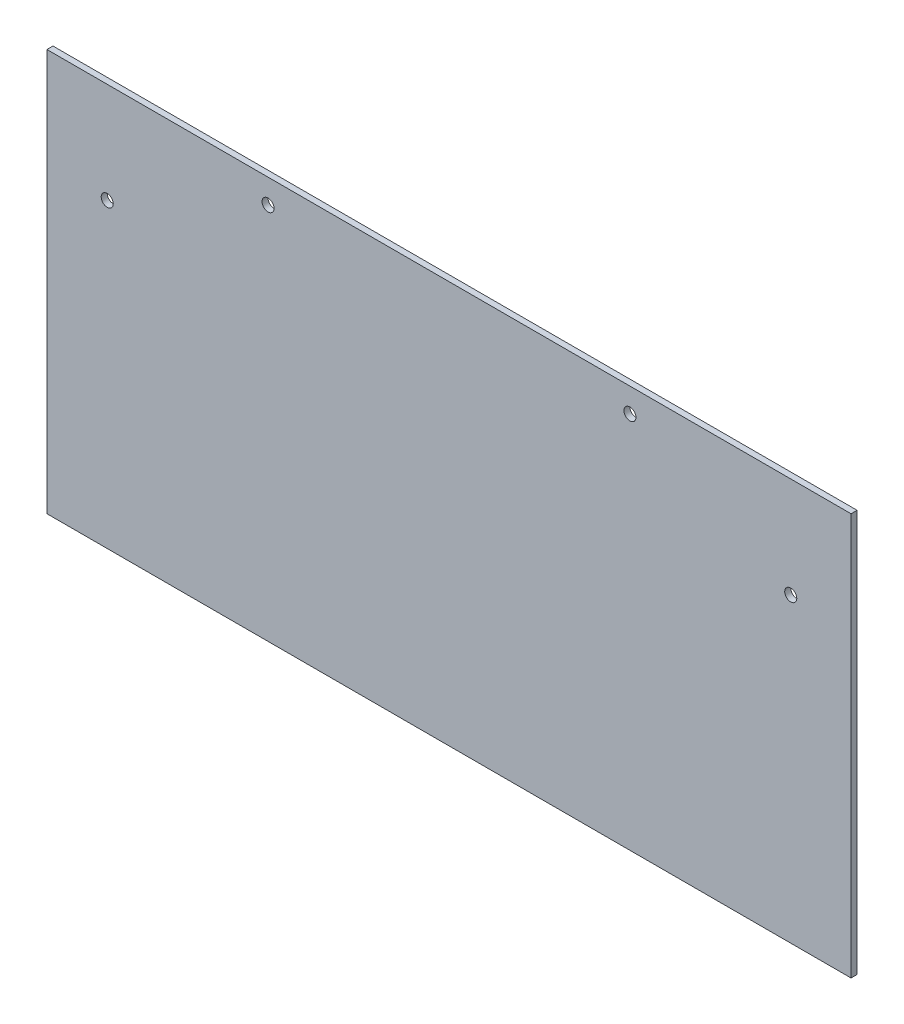
SolidWorks part; units mm, degrees
ref_plane "Front Plane" through (0, 0, 0) normal (0, 0, 1) x (1, 0, 0)
ref_plane "Top Plane" through (0, 0, 0) normal (0, 1, 0) x (1, 0, 0)
ref_plane "Right Plane" through (0, 0, 0) normal (1, 0, 0) x (0, 0, -1)
sketch "Sketch1" plane through (0, 0, 0) normal (0, 0, 1) x (1, 0, 0)
  line L1 (0, 0) -> (200, 0)
  line L2 (0, 0) -> (0, 100)
  line L3 (0, 100) -> (200, 100)
  line L4 (200, 0) -> (200, 100)
  dimension "D1" = 200
  dimension "D2" = 100
extrude "Boss-Extrude1" add sketch "Sketch1" along normal blind 1.5 contours L3 L4 L1 L2
hole_wizard "Ø3.0mm Dowel Hole2" positions "Sketch4" profile "Sketch5" hole size "Ø3.0" standard "ANSI Metric" end condition through all
sketch "Sketch4" plane through (0, 0, 1.5) normal (0, 0, 1) x (1, 0, 0)
  line L0 (0, 100) -> (200, 100) construction
  line L1 (0, 0) -> (0, 100) construction
  line L2 (200, 0) -> (200, 100) construction
  point P0 (15, 75)
  point P2 (185, 75)
  dimension "D1" = 25
  dimension "D2" = 15
  dimension "D3" = 25
  dimension "D4" = 15
sketch "Sketch5" plane through (15, 75, 1.5) normal (1, 0, 0) x (0, -1, 0)
  line L0 (0, 0) -> (0, 1.5)
  line L1 (0, 1.5) -> (1.5, 1.5)
  line L2 (1.5, 1.5) -> (1.5, 0)
  line L5 (1.5, 0) -> (0, 0)
  line L11 (0, -6.35) -> (0, 107.95) construction
  dimension "Thru Hole Dia." = 3
  dimension "Thru Hole Depth" = 1.5
hole_wizard "Ø3.0mm Dowel Hole3" positions "Sketch6" profile "Sketch7" hole size "Ø3.0" standard "ANSI Metric" end condition through all
sketch "Sketch6" plane through (0, 0, 1.5) normal (0, 0, 1) x (1, 0, 0)
  line L0 (0, 100) -> (200, 100) construction
  line L1 (0, 0) -> (0, 100) construction
  point P0 (55, 94)
  point P2 (145, 94)
  dimension "D1" = 6
  dimension "D2" = 6
  dimension "D3" = 90
  dimension "D4" = 55
sketch "Sketch7" plane through (55, 94, 1.5) normal (1, 0, 0) x (0, -1, 0)
  line L0 (0, 0) -> (0, 1.5)
  line L1 (0, 1.5) -> (1.5, 1.5)
  line L2 (1.5, 1.5) -> (1.5, 0)
  line L5 (1.5, 0) -> (0, 0)
  line L11 (0, -6.35) -> (0, 107.95) construction
  dimension "Thru Hole Dia." = 3
  dimension "Thru Hole Depth" = 1.5
